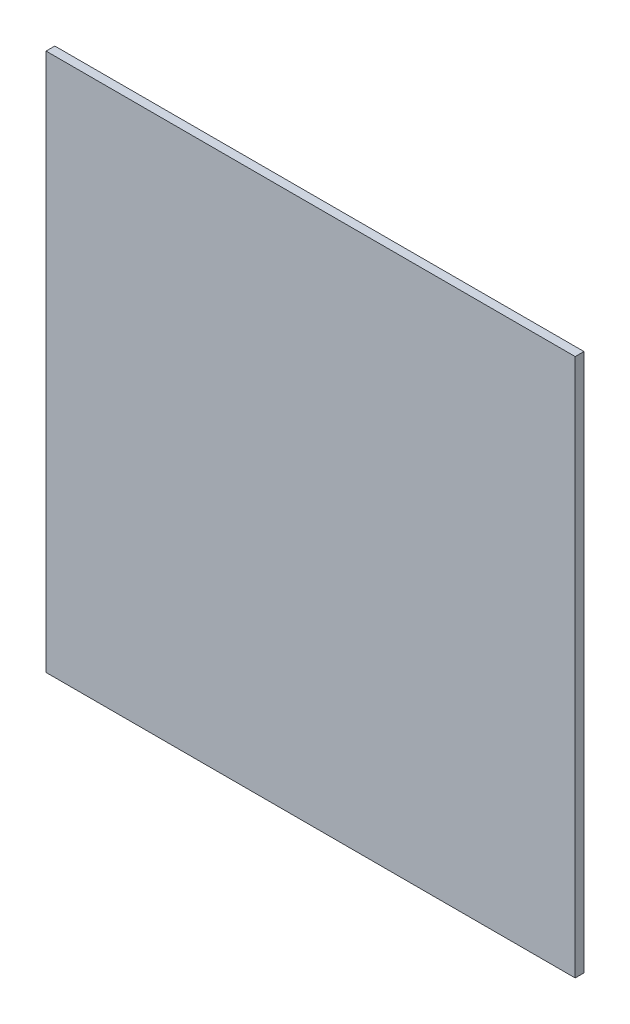
SolidWorks part; units mm, degrees
ref_plane "Alzado" through (0, 0, 0) normal (0, 0, 1) x (1, 0, 0)
ref_plane "Planta" through (0, 0, 0) normal (0, 1, 0) x (1, 0, 0)
ref_plane "Vista lateral" through (0, 0, 0) normal (1, 0, 0) x (0, 0, -1)
sketch "Croquis1" plane through (0, 0, 0) normal (0, 0, 1) x (1, 0, 0)
  line L1 (302.35, -307.5) -> (-302.35, -307.5)
  line L2 (302.35, -307.5) -> (302.35, 307.5)
  line L3 (302.35, 307.5) -> (-302.35, 307.5)
  line L4 (-302.35, -307.5) -> (-302.35, 307.5)
  line L5 (302.35, -307.5) -> (-302.35, 307.5) construction
  line L6 (302.35, 307.5) -> (-302.35, -307.5) construction
  point P0 (0, 0)
  dimension "D1" = 615
  dimension "D2" = 604.7
extrude "Saliente-Extruir1" add sketch "Croquis1" along normal blind 10
